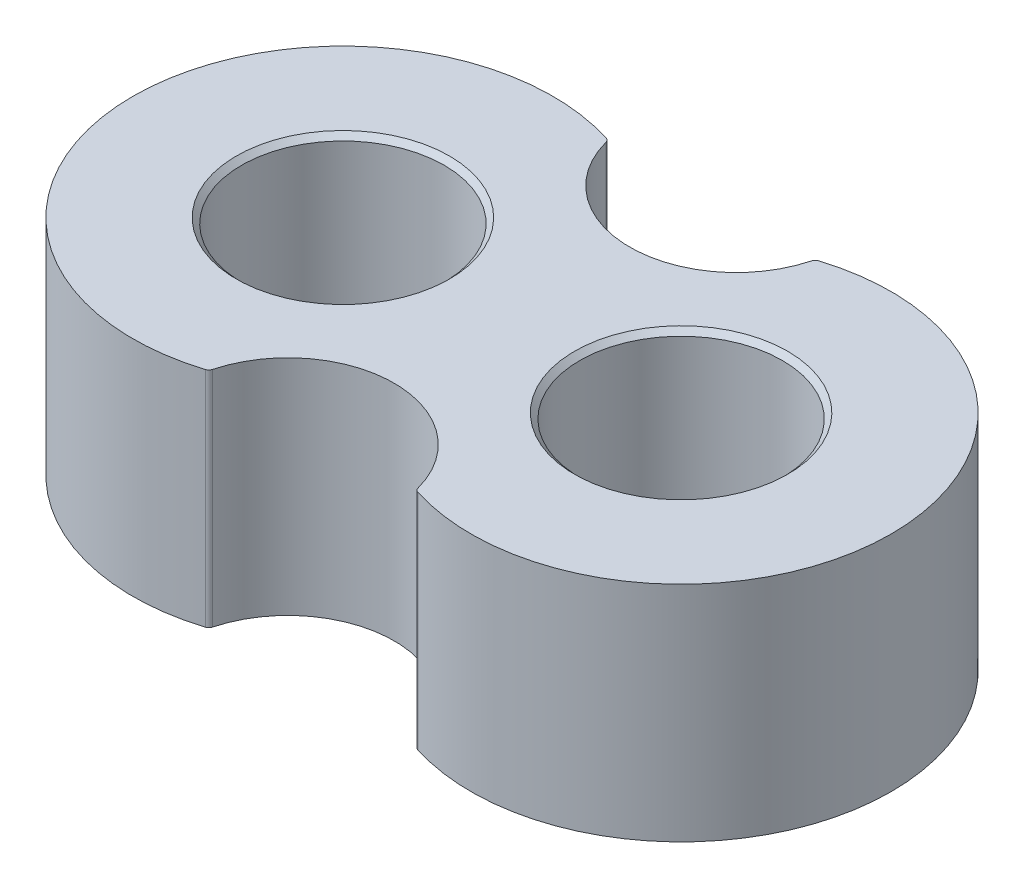
SolidWorks part; units mm, degrees
ref_plane "Front Plane" through (0, 0, 0) normal (0, 0, 1) x (1, 0, 0)
ref_plane "Top Plane" through (0, 0, 0) normal (0, 1, 0) x (1, 0, 0)
ref_plane "Right Plane" through (0, 0, 0) normal (1, 0, 0) x (0, 0, -1)
sketch "Sketch1" plane through (0, 0, 0) normal (0, 1, 0) x (1, 0, 0)
  line L0 (0, 17.2626) -> (0, 11.075) construction
  line L1 (-15.9, 0) -> (15.9, 0) construction
  line L2 (0, 10.5514) -> (0, 0) construction
  arc A1 (-9.6624, 18.4986) -> (9.6624, 18.4986) centre (0, 21.075) ccw
  arc A2 (-9.6624, -18.4986) -> (9.6624, -18.4986) centre (0, -21.075) cw
  arc A4 (-9.9961, -18.8469) -> (-9.9961, 18.8469) centre (-15.9, 0) cw
  arc A5 (9.9961, -18.8469) -> (9.9961, 18.8469) centre (15.9, 0) ccw
  arc A6 (-9.6624, -18.4986) -> (-9.9961, -18.8469) centre (-10.1455, -18.3698) cw
  arc A7 (9.6624, -18.4986) -> (9.9961, -18.8469) centre (10.1455, -18.3698) ccw
  arc A8 (9.9961, 18.8469) -> (9.6624, 18.4986) centre (10.1455, 18.3698) ccw
  arc A9 (-9.9961, 18.8469) -> (-9.6624, 18.4986) centre (-10.1455, 18.3698) cw
  circle A10 centre (-15.9, 0) radius 9.525
  circle A11 centre (15.9, 0) radius 9.525
  point P27 (0, 0)
  point P28 (0, 0)
  dimension "D1" = 0.5
  dimension "D3" = 20
  dimension "D5" = 19.05
  dimension "D6" = 19.05
  dimension "D10" = 19.75
  dimension "D7" = 19.75
  dimension "D2" = 15.9
  dimension "D4" = 21.075
  dimension "D8" = 15.9
  dimension "D9" = 15.9
extrude "Boss-Extrude1" add sketch "Sketch1" along normal blind 20.985
chamfer "Chamfer1" distance 0.5 angle 45 4 edges at (-15.9, 0, 9.525) (15.9, 0, 9.525) (15.9, 20.985, 9.525) (-15.9, 20.985, 9.525)
